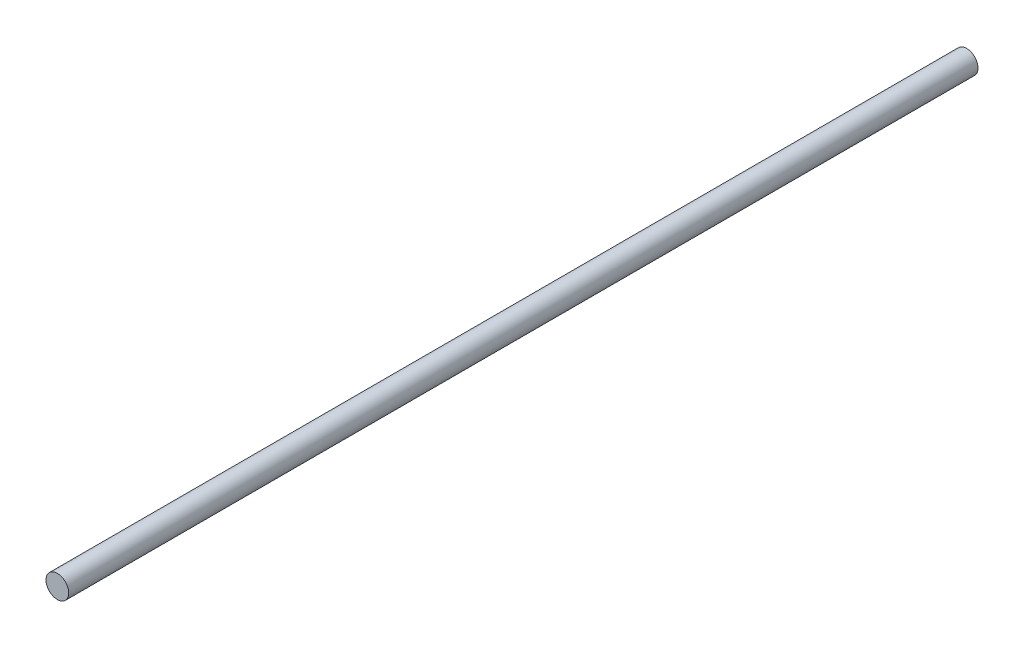
SolidWorks part; units mm, degrees
ref_plane "Plan de face" through (0, 0, 0) normal (0, 0, 1) x (1, 0, 0)
ref_plane "Plan de dessus" through (0, 0, 0) normal (0, 1, 0) x (1, 0, 0)
ref_plane "Plan de droite" through (0, 0, 0) normal (1, 0, 0) x (0, 0, -1)
sketch "Esquisse1" plane through (0, 0, 0) normal (0, 0, 1) x (1, 0, 0)
  circle A0 centre (0, 0) radius 7.5
  dimension "D1" = 15
extrude "Boss.-Extru.1" add sketch "Esquisse1" along normal blind 600
